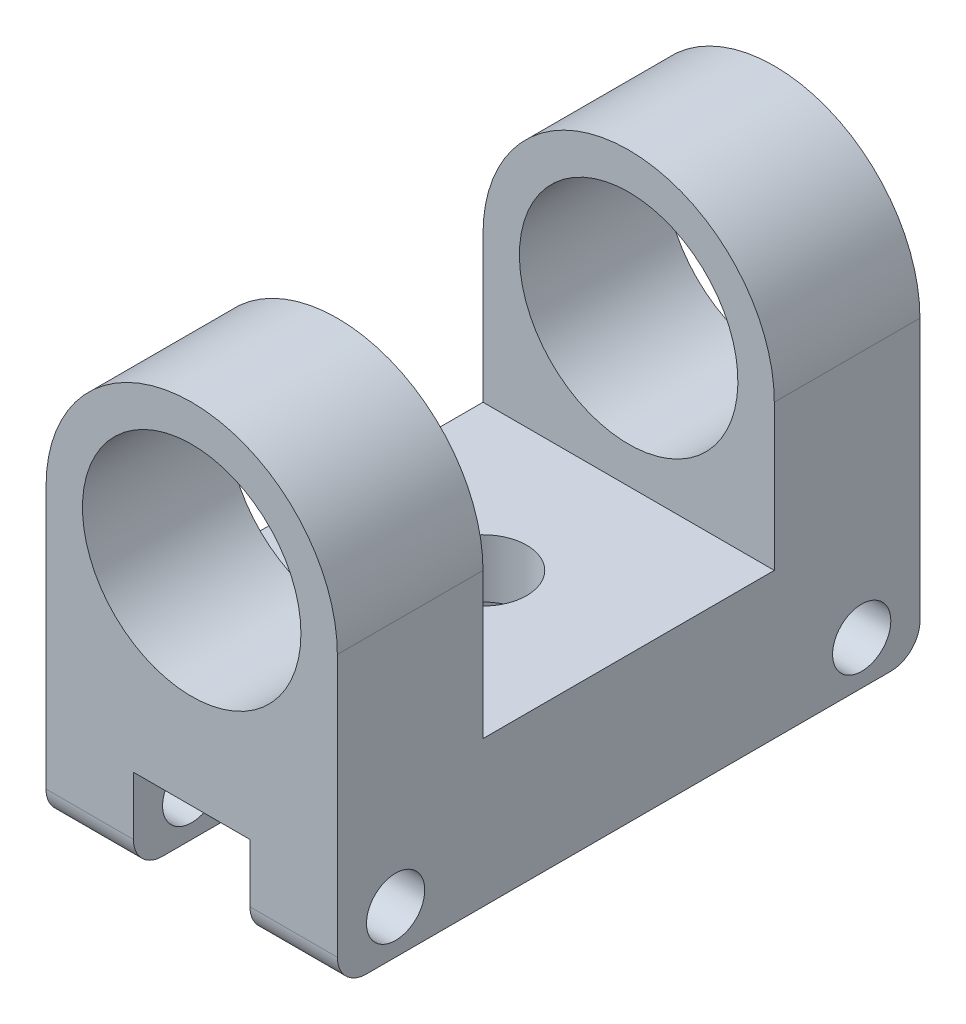
SolidWorks part; units mm, degrees
ref_plane "Front Plane" through (0, 0, 0) normal (0, 0, 1) x (1, 0, 0)
ref_plane "Top Plane" through (0, 0, 0) normal (0, 1, 0) x (1, 0, 0)
ref_plane "Right Plane" through (0, 0, 0) normal (1, 0, 0) x (0, 0, -1)
sketch "Sketch2" plane through (0, 0, 0) normal (0, 0, 1) x (1, 0, 0)
  line L0 (30, 0) -> (30, 30)
  line L1 (0, 0) -> (30, 0)
  line L2 (0, 0) -> (0, 100)
  line L4 (100, 0) -> (100, 100)
  line L5 (30, 30) -> (70, 30)
  line L6 (70, 30) -> (70, 0)
  line L7 (70, 0) -> (100, 0)
  arc A0 (100, 100) -> (0, 100) centre (50, 100) ccw
  circle A1 centre (50, 100) radius 37.5
  dimension "D6" = 50
  dimension "D7" = 75
  dimension "D1" = 100
  dimension "D2" = 100
  dimension "D3" = 70
  dimension "D4" = 30
  dimension "D5" = 30
extrude "Boss-Extrude3" add sketch "Sketch2" along normal blind 200 contours L4 L7 L6 L5 L0 L1 L2 A0 | A1
sketch "Sketch5" plane through (100, 0, 0) normal (1, 0, 0) x (0, 0, -1)
  line L0 (0, 150) -> (-200, 150) construction
  line L2 (-150, 150) -> (-150, 50)
  line L3 (-150, 50) -> (-50, 50)
  line L4 (-50, 150) -> (-50, 50)
  line L5 (-150, 150) -> (-50, 150)
  dimension "D1" = 150
  dimension "D2" = 50
  dimension "D3" = 50
extrude "Cut-Extrude2" cut sketch "Sketch5" against normal through all
sketch "Sketch6" plane through (100, 0, 0) normal (1, 0, 0) x (0, 0, -1)
  circle A0 centre (-180, 15) radius 10
  circle A1 centre (-20, 15) radius 10
  dimension "D2" = 20
  dimension "D1" = 15
  dimension "D3" = 20
  dimension "D4" = 180
extrude "Cut-Extrude3" cut sketch "Sketch6" against normal through all contours A0 | A1
fillet "Fillet1" radius 10 4 edges at (15, 0, 0) (85, 0, 0) (15, 0, 200) (85, 0, 200)
sketch "Sketch7" plane through (0, 50, 0) normal (0, 1, 0) x (1, 0, 0)
  line L0 (0, -200) -> (100, -200) construction
  line L2 (0, -150) -> (0, -50) construction
  circle A0 centre (50, -100) radius 15
  dimension "D1" = 30
  dimension "D2" = 100
  dimension "D3" = 50
extrude "Cut-Extrude4" cut sketch "Sketch7" against normal through all contours A0
